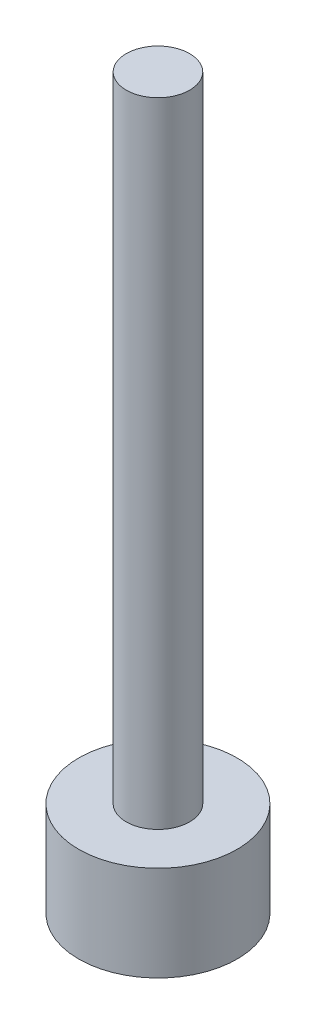
SolidWorks part; units mm, degrees
ref_plane "Front Plane" through (0, 0, 0) normal (0, 0, 1) x (1, 0, 0)
ref_plane "Top Plane" through (0, 0, 0) normal (0, 1, 0) x (1, 0, 0)
ref_plane "Right Plane" through (0, 0, 0) normal (1, 0, 0) x (0, 0, -1)
sketch "Sketch2" plane through (0, 0, 0) normal (0, 1, 0) x (1, 0, 0)
  circle A0 centre (0, 0) radius 2.5
extrude "Boss-Extrude1" add sketch "Sketch2" along normal blind 3
sketch "Sketch3" plane through (0, 3, 0) normal (0, 1, 0) x (1, 0, 0)
  circle A0 centre (0, 0) radius 1
extrude "Boss-Extrude2" add sketch "Sketch3" along normal blind 20 contours A0
